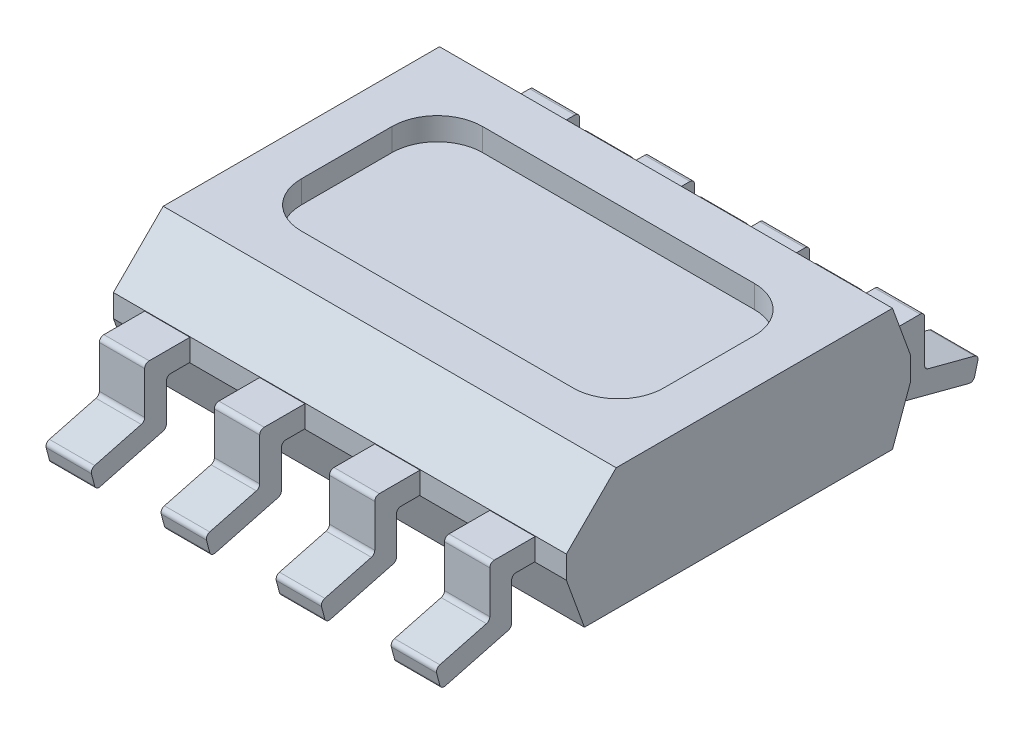
SolidWorks part; units mm, degrees
ref_plane "Front Plane" through (0, 0, 0) normal (0, 0, 1) x (1, 0, 0)
ref_plane "Top Plane" through (0, 0, 0) normal (0, 1, 0) x (1, 0, 0)
ref_plane "Right Plane" through (0, 0, 0) normal (1, 0, 0) x (0, 0, -1)
sketch "Sketch1" plane through (0, 0, 0) normal (0, 1, 0) x (1, 0, 0)
  line L1 (0, 0) -> (5, 0)
  line L2 (0, 0) -> (0, 3.8)
  line L3 (0, 3.8) -> (5, 3.8)
  line L4 (5, 0) -> (5, 3.8)
  dimension "D1" = 5
  dimension "D2" = 3.8
extrude "Boss-Extrude1" add sketch "Sketch1" along normal blind 1.35
sketch "Sketch2" plane through (5, 0, 0) normal (1, 0, 0) x (0, 0, -1)
  line L0 (0.55, 1.35) -> (0, 0.8)
  line L1 (0, 1.35) -> (3.8, 1.35) construction
  line L2 (0, 1.35) -> (0, 0) construction
  line L3 (0, 0.8) -> (0, 0.55)
  line L4 (0, 0.55) -> (0.2, 0)
  line L5 (0, 0) -> (3.8, 0) construction
  line L6 (0.2, 0) -> (3.6, 0)
  line L7 (3.6, 0) -> (3.8, 0.55)
  line L8 (3.8, 1.35) -> (3.8, 0) construction
  line L9 (3.8, 0.55) -> (3.8, 0.8)
  line L10 (3.8, 0.8) -> (3.6, 1.35)
  line L11 (3.6, 1.35) -> (0.55, 1.35)
  line M9 (0, 0) -> (3.8, 0)
  line M10 (3.8, 0) -> (3.8, 1.35)
  line M11 (3.8, 1.35) -> (0, 1.35)
  line M12 (0, 1.35) -> (0, 0)
  dimension "D1" = 0.55
  dimension "D2" = 0.25
  dimension "D3" = 0.25
  dimension "D4" = 0.55
  dimension "D5" = 0.55
  dimension "D6" = 0.55
  dimension "D7" = 0.2
  dimension "D8" = 0.2
  dimension "D9" = 0.2
extrude "Cut-Extrude1" cut sketch "Sketch2" against normal blind 5 contours L0 M11 M12 | L4 M12 M9 | L7 M9 M10 | L10 M10 M11
sketch "Sketch3" plane through (0, 1.35, 0) normal (0, 1, 0) x (1, 0, 0)
  line L0 (0, 3.6) -> (0, 0.55) construction
  line L1 (1, 3.075) -> (4, 3.075)
  line L2 (0.5, 2.575) -> (0.5, 1.575)
  line L3 (1, 1.075) -> (4, 1.075)
  line L4 (4.5, 2.575) -> (4.5, 1.575)
  line L5 (0, 3.6) -> (5, 3.6) construction
  line L7 (0, 0.55) -> (5, 0.55) construction
  arc A0 (0.5, 1.575) -> (1, 1.075) centre (1, 1.575) ccw
  arc A1 (4, 1.075) -> (4.5, 1.575) centre (4, 1.575) ccw
  arc A2 (4, 3.075) -> (4.5, 2.575) centre (4, 2.575) cw
  arc A3 (0.5, 2.575) -> (1, 3.075) centre (1, 2.575) cw
  point P14 (4.5, 1.075)
  point P17 (4.5, 3.075)
  point P20 (0.5, 3.075)
  dimension "D6" = 0.5
  dimension "D1" = 4
  dimension "D2" = 2
  dimension "D3" = 0.5
  dimension "D4" = 0.525
  dimension "D5" = 0.525
extrude "Cut-Extrude2" cut sketch "Sketch3" against normal blind 0.25
ref_plane "Plane1" through (4.405, 0, 0) normal (1, 0, 0) x (0, 0, -1)
sketch "Sketch4" plane through (4.405, 0, 0) normal (1, 0, 0) x (0, 0, -1)
  line L0 (3.8, 0.795) -> (4.25, 0.795)
  line L1 (3.8, 0.8) -> (3.8, 0.55) construction
  line L2 (4.3, 0.745) -> (4.3, 0.2786)
  line L3 (4.3373, 0.2302) -> (4.8516, 0.0948)
  line L4 (4.8873, 0.0337) -> (4.8516, -0.1016)
  line L5 (4.7906, -0.1373) -> (4.0973, 0.0452)
  line L6 (4.06, 0.0935) -> (4.06, 0.505)
  line L7 (4.01, 0.555) -> (3.8, 0.555)
  line L8 (3.8, 0.555) -> (3.8, 0.795)
  arc A0 (4.8516, -0.1016) -> (4.7906, -0.1373) centre (4.8033, -0.0889) cw
  arc A1 (4.8516, 0.0948) -> (4.8873, 0.0337) centre (4.8389, 0.0465) cw
  arc A2 (4.0973, 0.0452) -> (4.06, 0.0935) centre (4.11, 0.0935) cw
  arc A3 (4.3, 0.2786) -> (4.3373, 0.2302) centre (4.35, 0.2786) ccw
  arc A4 (4.06, 0.505) -> (4.01, 0.555) centre (4.01, 0.505) ccw
  arc A5 (4.25, 0.795) -> (4.3, 0.745) centre (4.25, 0.745) cw
  point P17 (4.8389, -0.15)
  point P20 (4.9, 0.0821)
  point P23 (4.06, 0.055)
  point P28 (4.06, 0.555)
  point P31 (4.3, 0.795)
  dimension "D9" = 0.05
  dimension "D1" = 1.1
  dimension "D2" = 0.15
  dimension "D3" = 0.24
  dimension "D4" = 0.24
  dimension "D5" = 0.24
  dimension "D6" = 0.005
  dimension "D7" = 0.5
  dimension "D8" = 0.5
extrude "Boss-Extrude2" add sketch "Sketch4" along normal mid plane 0.5
pattern_linear "LPattern1" count 4 spacing 1.27 along (-1, 0, 0) of "Boss-Extrude2"
ref_plane "Plane2" through (0, 0, -2.075) normal (0, 0, -1) x (-1, 0, 0)
sketch "Sketch6" plane through (5, 0, 0) normal (1, 0, 0) x (0, 0, -1)
  line L0 (0, 0.8) -> (3.8, 0.8) construction
  line L1 (3.8, 0.8) -> (3.8, 0.55) construction
  line L2 (3.8, 0.55) -> (0, 0.55) construction
  line L3 (1.9, 0.8) -> (1.9, 0.55)
sketch "Sketch7" plane through (0, 0, 0) normal (-1, 0, 0) x (0, 0, 1)
  line L0 (-3.8, 0.8) -> (0, 0.8) construction
  line L1 (-1.9, 0.8) -> (-1.9, 0.675)
  line L2 (-1.9, 0.8) -> (-1.9, 0.55) construction
  line L3 (-1.9, 0.675) -> (-2.2759, 0.675)
  line L4 (-2.2759, 0.675) -> (-3.8, 1.4846)
ref_plane "Plane3" through (0, 0, -1.9) normal (0, 0, -1) x (-1, 0, 0)
mirror "Mirror1" about plane through (0, 0, -1.9) normal (0, 0, -1) of "Boss-Extrude2", "LPattern1"
